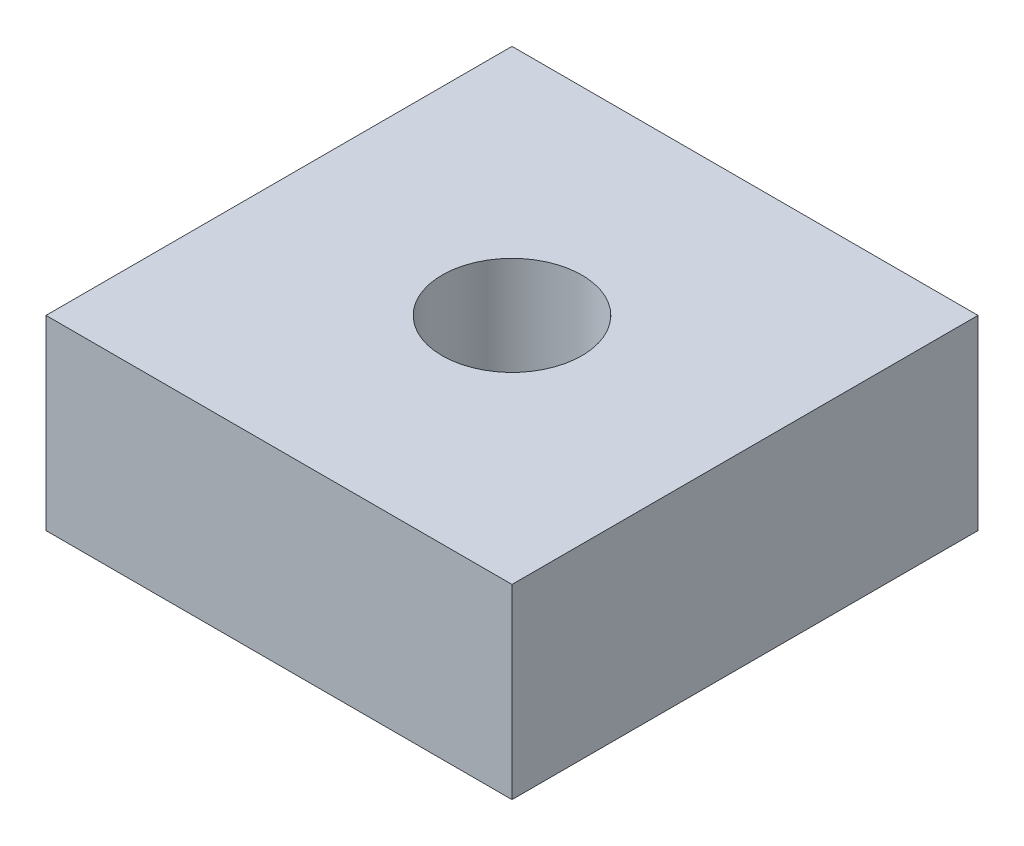
SolidWorks part; units mm, degrees
material "Phosphor bronze 10% D, UNS C52400"
ref_plane "Front Plane" through (0, 0, 0) normal (0, 0, 1) x (1, 0, 0)
ref_plane "Top Plane" through (0, 0, 0) normal (0, 1, 0) x (1, 0, 0)
ref_plane "Right Plane" through (0, 0, 0) normal (1, 0, 0) x (0, 0, -1)
sketch "Sketch1" plane through (0, 0, 0) normal (0, 1, 0) x (1, 0, 0)
  line L1 (-25, -25) -> (25, -25)
  line L2 (-25, -25) -> (-25, 25)
  line L3 (-25, 25) -> (25, 25)
  line L4 (25, -25) -> (25, 25)
  line L5 (-25, -25) -> (25, 25) construction
  line L6 (-25, 25) -> (25, -25) construction
  circle A0 centre (0, 0) radius 7.5
  point P0 (0, 0)
  dimension "D3" = 15
  dimension "D1" = 50
  dimension "D2" = 50
extrude "Boss-Extrude1" add sketch "Sketch1" along normal mid plane 20
